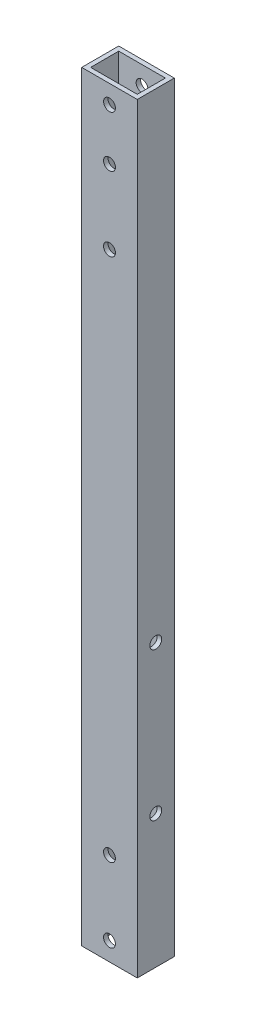
SolidWorks part; units mm, degrees
ref_plane "正面" through (0, 0, 0) normal (0, 0, 1) x (1, 0, 0)
ref_plane "平面" through (0, 0, 0) normal (0, 1, 0) x (1, 0, 0)
ref_plane "右側面" through (0, 0, 0) normal (1, 0, 0) x (0, 0, -1)
sketch "ｽｹｯﾁ1" plane through (0, 0, 0) normal (0, 1, 0) x (1, 0, 0)
  line L0 (-6.3, 3.8) -> (6.3, 3.8)
  line L1 (-7.5, 5) -> (7.5, 5)
  line L2 (-7.5, 5) -> (-7.5, -5)
  line L3 (-7.5, -5) -> (7.5, -5)
  line L4 (7.5, 5) -> (7.5, -5)
  line L5 (-7.5, 5) -> (7.5, -5) construction
  line L6 (-7.5, -5) -> (7.5, 5) construction
  line L7 (6.3, 3.8) -> (6.3, -3.8)
  line L8 (-6.3, -3.8) -> (6.3, -3.8)
  line L9 (-6.3, 3.8) -> (-6.3, -3.8)
  point P0 (0, 0)
  dimension "D1" = 15
  dimension "D2" = 10
  dimension "D3" = 1.2
extrude "ﾎﾞｽ - 押し出し1" add sketch "ｽｹｯﾁ1" along normal mid plane 220
sketch "ｽｹｯﾁ2" plane through (0, 0, -5) normal (0, 0, -1) x (-1, 0, 0)
  line L0 (0, -110) -> (0, -85) construction
  line L1 (-7.5, -110) -> (7.5, -110) construction
  circle A0 centre (0, -85) radius 1.6
  circle A1 centre (0, -105) radius 1.6
  dimension "D2" = 3.2
  dimension "D3" = 3.2
  dimension "D1" = 25
  dimension "D4" = 20
extrude "ｶｯﾄ - 押し出し1" cut sketch "ｽｹｯﾁ2" against normal blind 100
sketch "ｽｹｯﾁ3" plane through (7.5, 0, 0) normal (1, 0, 0) x (0, 0, -1)
  line L1 (0, -110) -> (0, 0) construction
  line L2 (-5, -110) -> (5, -110) construction
  line L4 (6.6334, -36.5) -> (31.6318, -36.5)
  line L5 (31.6318, -36.5) -> (31.6318, -31.5)
  line L6 (31.6318, -31.5) -> (6.6334, -31.5)
  line L7 (6.6334, -31.5) -> (6.6334, -36.5)
  line L8 (6.6334, -36.5) -> (31.6318, -36.5) construction
  line L10 (31.6318, -31.5) -> (6.6334, -31.5) construction
  line L11 (6.6334, -31.5) -> (6.6334, -36.5) construction
  line L12 (6.6334, -76.5) -> (31.6318, -76.5)
  line L13 (31.6318, -76.5) -> (31.6318, -71.5)
  line L14 (31.6318, -71.5) -> (6.6334, -71.5)
  line L15 (6.6334, -71.5) -> (6.6334, -76.5)
  line L16 (6.6334, -76.5) -> (31.6318, -76.5) construction
  line L18 (31.6318, -71.5) -> (6.6334, -71.5) construction
  line L19 (6.6334, -71.5) -> (6.6334, -76.5) construction
  line L26 (31.6318, -36.5) -> (31.6318, -31.5)
  line L27 (31.6318, -76.5) -> (31.6318, -71.5)
  circle A0 centre (0, -34) radius 1.6
  circle A1 centre (0, -74) radius 1.6
  dimension "D3" = 3.2
  dimension "D4" = 3.2
  dimension "D5" = 36
  dimension "D6" = 40
  dimension "D1" = 0
  dimension "D2" = 0
extrude "ｶｯﾄ - 押し出し2" cut sketch "ｽｹｯﾁ3" against normal blind 15 contours A0 | A1
sketch "ｽｹｯﾁ5" plane through (0, 110, 0) normal (0, 1, 0) x (1, 0, 0)
  line L4 (7.5, -5) -> (7.5, 5)
  line L5 (7.5, 5) -> (-7.5, 5)
  line L6 (-7.5, 5) -> (-7.5, -5)
  line L7 (-7.5, -5) -> (7.5, -5)
  line L8 (7.5, -5) -> (7.5, 5)
  line L9 (7.5, 5) -> (-7.5, 5)
  line L10 (-7.5, 5) -> (-7.5, -5)
  line L11 (-7.5, -5) -> (7.5, -5)
  dimension "D1" = 0
extrude "ｶｯﾄ - 押し出し4" cut sketch "ｽｹｯﾁ5" against normal blind 14.5
sketch "ｽｹｯﾁ6" plane through (0, 0, -5) normal (0, 0, -1) x (-1, 0, 0)
  line L0 (0, 95.5) -> (0, 90.5) construction
  line L1 (-7.5, 95.5) -> (7.5, 95.5) construction
  line L2 (0, 90.5) -> (0, 76.66) construction
  line L3 (0, 76.66) -> (0, 56.66) construction
  circle A0 centre (0, 90.5) radius 1.6
  circle A1 centre (0, 76.66) radius 1.6
  circle A2 centre (0, 56.66) radius 1.6
  dimension "D2" = 3.2
  dimension "D5" = 3.2
  dimension "D6" = 3.2
  dimension "D1" = 5
  dimension "D3" = 13.84
  dimension "D4" = 20
extrude "ｶｯﾄ - 押し出し5" cut sketch "ｽｹｯﾁ6" against normal blind 15
